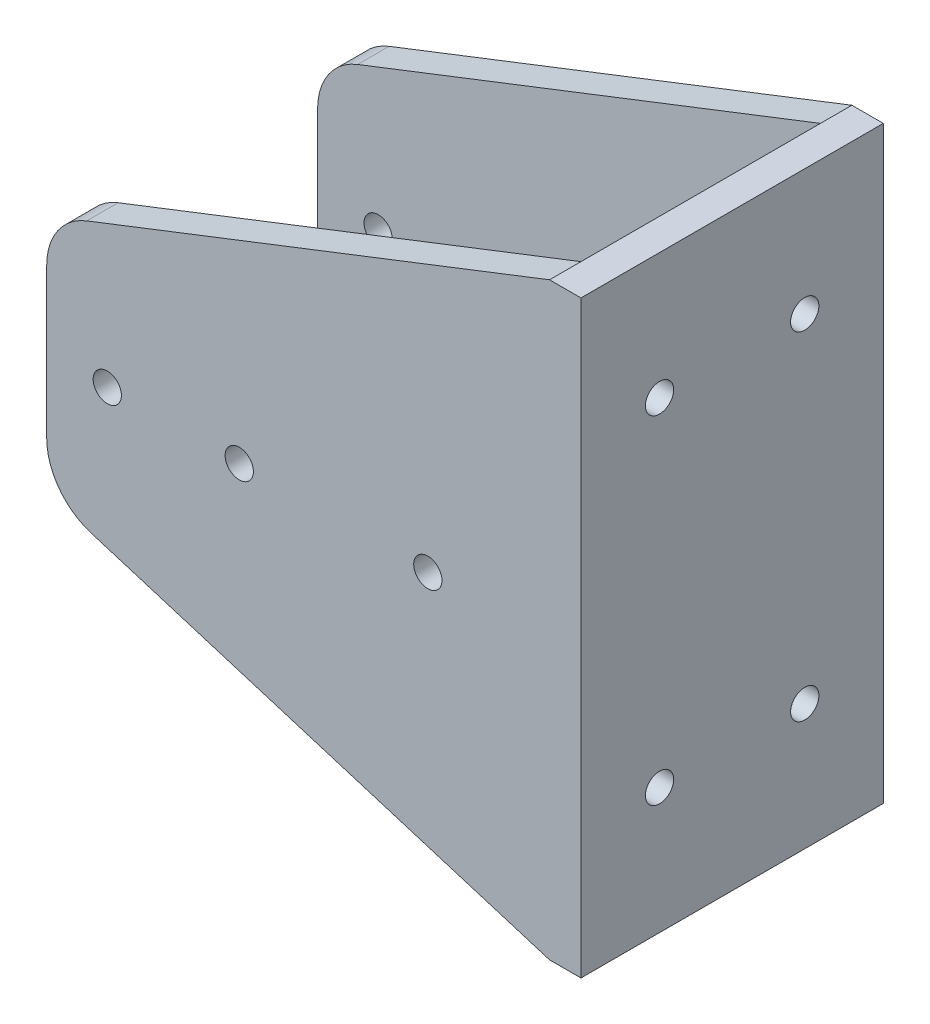
SolidWorks part; units mm, degrees
ref_plane "Front Plane" through (0, 0, 0) normal (0, 0, 1) x (1, 0, 0)
ref_plane "Top Plane" through (0, 0, 0) normal (0, 1, 0) x (1, 0, 0)
ref_plane "Right Plane" through (0, 0, 0) normal (1, 0, 0) x (0, 0, -1)
sketch "Sketch1" plane through (0, 0, 0) normal (0, 0, 1) x (1, 0, 0)
  line L2 (-52.1606, -11.8043) -> (-52.1606, 11.9845)
  line L5 (-45.792, 21.3018) -> (27.8394, 50)
  line L20 (27.8394, -43.668) -> (-45.085, -21.3671)
  line L21 (27.8394, -43.668) -> (27.8394, 50)
  circle A0 centre (-42.5238, 0) radius 2.25
  circle A1 centre (-21.5238, 0) radius 2.25
  circle A2 centre (8.4762, 0) radius 2.25
  arc A5 (-52.1606, -11.8043) -> (-45.085, -21.3671) centre (-42.1606, -11.8043) ccw
  arc A6 (-52.1606, 11.9845) -> (-45.792, 21.3018) centre (-42.1606, 11.9845) cw
  point P0 (0, 0)
  dimension "D3" = 4.5
  dimension "D4" = 4.5
  dimension "D5" = 4.5
  dimension "D11" = 9.6368
  dimension "D2" = 10
  dimension "D6" = 21
  dimension "D9" = 30
extrude "Boss-Extrude1" add sketch "Sketch1" along normal blind 5
sketch "Sketch2" plane through (27.8394, 0, 0) normal (1, 0, 0) x (0, 0, -1)
  line L5 (0, 50) -> (-48.1, 50)
  line L6 (0, 50) -> (0, -43.7)
  line L7 (0, -43.7) -> (-48.1, -43.7)
  line L8 (-48.1, 50) -> (-48.1, -43.7)
  circle A0 centre (-35.6, 30) radius 2.25
  circle A1 centre (-12.5, 30) radius 2.25
  circle A2 centre (-35.6, -23.7) radius 2.25
  circle A3 centre (-12.5, -23.7) radius 2.25
  dimension "D2" = 48.1
  dimension "D3" = 20
  dimension "D4" = 20
  dimension "D5" = 20
  dimension "D7" = 4.5
  dimension "D8" = 4.5
  dimension "D9" = 4.5
  dimension "D10" = 4.5
  dimension "D1" = 93.7
  dimension "D6" = 20
extrude "Boss-Extrude2" add sketch "Sketch2" along normal blind 5
sketch "Sketch3" plane through (0, 0, 48.1) normal (0, 0, 1) x (1, 0, 0)
  line L0 (27.8394, 50) -> (-45.792, 21.3018)
  line L1 (-52.1606, -11.8043) -> (-52.1606, 11.9845)
  line L2 (27.8394, 50) -> (27.8394, -43.7)
  line L3 (27.8394, -43.7) -> (-45.085, -21.3671)
  circle A0 centre (-21.5238, 0) radius 2.25
  circle A1 centre (-42.5238, 0) radius 2.25
  circle A2 centre (8.4762, 0) radius 2.25
  arc A3 (-52.1606, 11.9845) -> (-45.792, 21.3018) centre (-42.1606, 11.9845) cw
  arc A4 (-45.085, -21.3671) -> (-52.1606, -11.8043) centre (-42.1606, -11.8043) cw
  dimension "D1" = 4.5
  dimension "D2" = 4.5
  dimension "D3" = 4.5
extrude "Boss-Extrude3" add sketch "Sketch3" against normal blind 5
